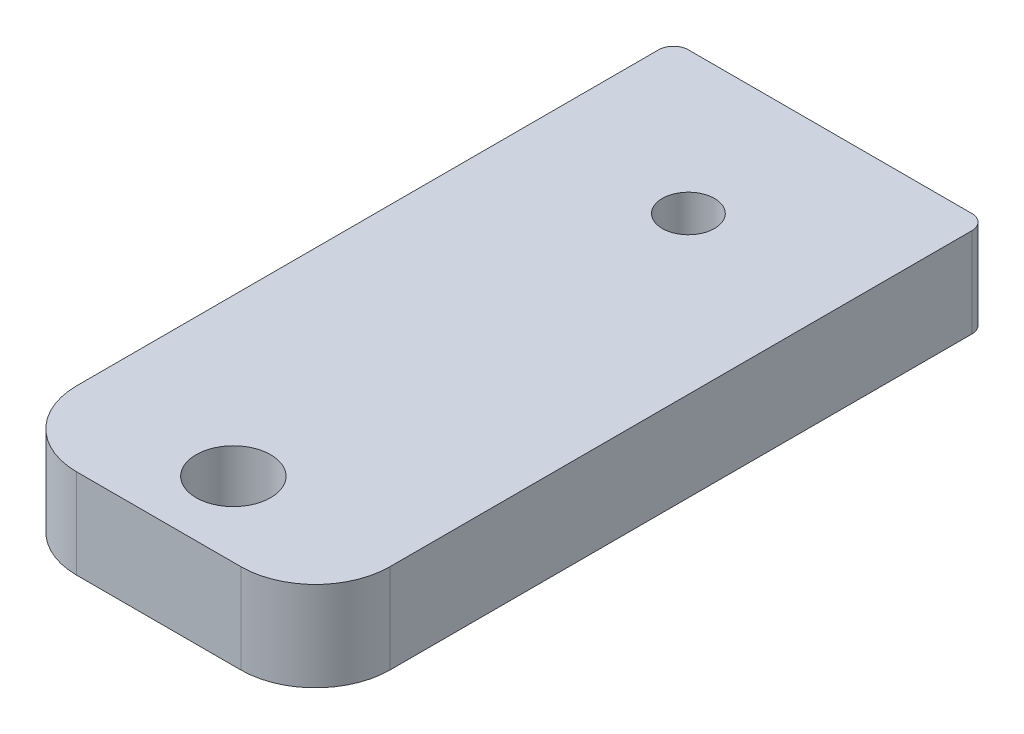
SolidWorks part; units mm, degrees
ref_plane "Front" through (0, 0, 0) normal (0, 0, 1) x (1, 0, 0)
ref_plane "Top" through (0, 0, 0) normal (0, 1, 0) x (1, 0, 0)
ref_plane "Right" through (0, 0, 0) normal (1, 0, 0) x (0, 0, -1)
sketch "Sketch1" plane through (0, 0, 0) normal (0, 1, 0) x (1, 0, 0)
  line L0 (-10.5, -13) -> (10.5, -13) construction
  line L1 (-5.5, -24.5) -> (5.5, -24.5)
  line L2 (-10.5, -19.5) -> (-10.5, 19.5)
  line L3 (-9.5, 20.5) -> (9.5, 20.5)
  line L4 (10.5, -19.5) -> (10.5, 19.5)
  line L5 (0, 20.5) -> (0, -24.5) construction
  line L6 (-10.5, 0) -> (10.5, 0) construction
  circle A0 centre (0, 11) radius 1.75
  arc A1 (5.5, -24.5) -> (10.5, -19.5) centre (5.5, -19.5) ccw
  arc A2 (-5.5, -24.5) -> (-10.5, -19.5) centre (-5.5, -19.5) cw
  arc A3 (9.5, 20.5) -> (10.5, 19.5) centre (9.5, 19.5) cw
  arc A4 (-10.5, 19.5) -> (-9.5, 20.5) centre (-9.5, 19.5) cw
  circle A5 centre (0, -19.5) radius 2.5
  point P0 (0, 0)
  point P19 (0, -19.5)
  point P20 (0, 0)
  dimension "D1" = 3.5
  dimension "D5" = 5
  dimension "D6" = 1
  dimension "D7" = 5
  dimension "D2" = 10.5
  dimension "D3" = 9.5
  dimension "D4" = 45
  dimension "D8" = 33.5
extrude "Boss-Extrude1" add sketch "Sketch1" along normal blind 6
